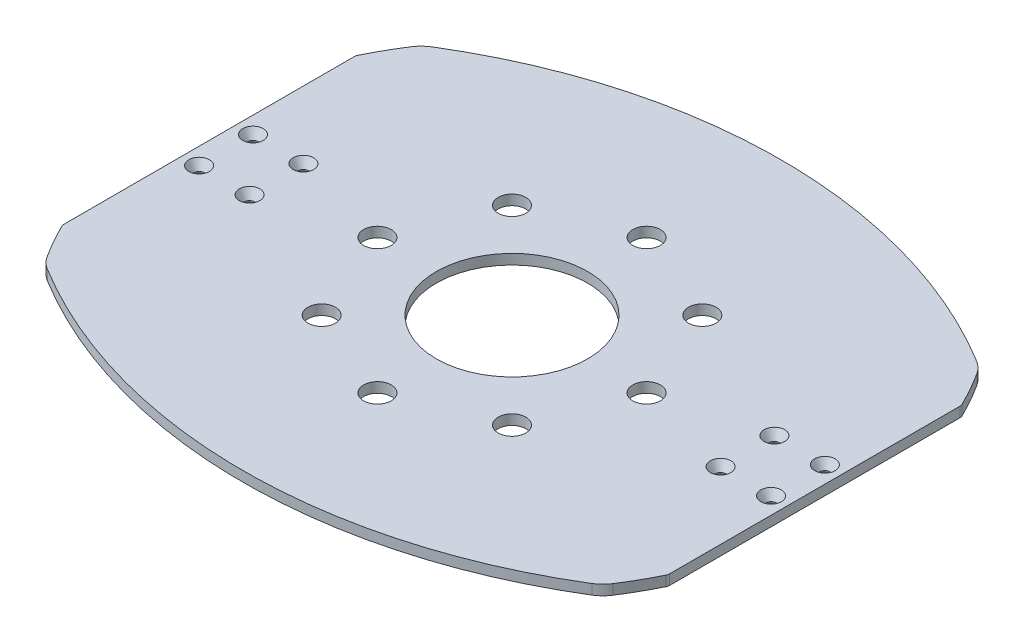
SolidWorks part; units mm, degrees
other "标注1"
sketch "草图6" plane through (-90, 3, -90) normal (0, 1, 0) x (1, 0, 0)
material "Thornel Mat VMA"
ref_plane "前视基准面" through (0, 0, 0) normal (0, 0, 1) x (1, 0, 0)
ref_plane "上视基准面" through (0, 0, 0) normal (0, 1, 0) x (1, 0, 0)
ref_plane "右视基准面" through (0, 0, 0) normal (1, 0, 0) x (0, 0, -1)
sketch "草图2" plane through (0, 0, 0) normal (0, 1, 0) x (1, 0, 0)
  line L1 (-90, 90) -> (90, 90)
  line L2 (-90, 90) -> (-90, -90)
  line L3 (-90, -90) -> (90, -90)
  line L4 (90, 90) -> (90, -90)
  line L5 (0, -90) -> (0, 90) construction
  line L6 (-90, 0) -> (90, 0) construction
  point P40 (0, 0)
  dimension "D1" = 180
  dimension "D2" = 180
extrude "凸台-拉伸1" add sketch "草图2" along normal blind 3
sketch "草图3" plane through (0, 3, 0) normal (0, 1, 0) x (1, 0, 0)
  circle A0 centre (0, 0) radius 40 construction
  circle A1 centre (0, 40) radius 4.1
  circle A2 centre (28.2843, 28.2843) radius 4.1
  circle A3 centre (40, 0) radius 4.1
  circle A4 centre (28.2843, -28.2843) radius 4.1
  circle A5 centre (0, -40) radius 4.1
  circle A6 centre (-28.2843, -28.2843) radius 4.1
  circle A7 centre (-40, 0) radius 4.1
  circle A8 centre (-28.2843, 28.2843) radius 4.1
  point P21 (0, 0)
  dimension "D1" = 80
  dimension "D2" = 8.2
  dimension "D3" = 8
extrude "切除-拉伸1" cut sketch "草图3" against normal blind 3
sketch "草图4" plane through (0, 3, 0) normal (0, 1, 0) x (1, 0, 0)
  circle A0 centre (0, 0) radius 100
  dimension "D1" = 200
extrude "切除-拉伸2" cut sketch "草图4" against normal blind 3 flip side to cut
sketch "草图5" plane through (0, 3, 0) normal (0, 1, 0) x (1, 0, 0)
  line L0 (0, 0) -> (-100, 0) construction
  line L1 (0, 0) -> (0, 95.2788) construction
  line L3 (-85, 8) -> (-70, 8) construction
  line L4 (-85, 8) -> (-85, -8) construction
  line L5 (-85, -8) -> (-70, -8) construction
  line L6 (-70, 8) -> (-70, -8) construction
  line L7 (-77.5, -8) -> (-77.5, 8) construction
  line L8 (-85, 0) -> (-70, 0) construction
  circle A0 centre (0, 0) radius 100 construction
  circle A5 centre (-85, 8) radius 1.55
  circle A6 centre (-70, 8) radius 1.55
  circle A7 centre (-85, -8) radius 1.55
  circle A8 centre (-70, -8) radius 1.55
  circle A9 centre (70, -8) radius 1.55
  circle A10 centre (85, -8) radius 1.55
  circle A11 centre (70, 8) radius 1.55
  circle A12 centre (85, 8) radius 1.55
  point P99 (-77.5, 0)
  dimension "D1" = 16
  dimension "D2" = 15
  dimension "D3" = 77.5
  dimension "D4" = 3.1
extrude "切除-拉伸3" cut sketch "草图5" against normal blind 3
fillet "圆角1" radius 2 8 edges at (-43.589, 1.5, 90) (43.589, 1.5, 90) (-90, 1.5, -43.589) (-90, 1.5, 43.589) (43.589, 1.5, -90) (-43.589, 1.5, -90) (90, 1.5, 43.589) (90, 1.5, -43.589)
sketch "草图7" plane through (0, 3, 0) normal (0, 1, 0) x (1, 0, 0)
  circle A0 centre (0, 0) radius 22.5
  dimension "D1" = 45
extrude "切除-拉伸4" cut sketch "草图7" against normal blind 10
sketch "草图8" plane through (0, 3, 0) normal (0, 1, 0) x (1, 0, 0)
  line L0 (0, 0) -> (0, -75) construction
  line L1 (0, 0) -> (306.2621, 0) construction
  line L2 (-43.1277, -90) -> (43.1277, -90) construction
  line L3 (43.1277, 90) -> (-43.1277, 90) construction
  line L4 (-43.1277, -90) -> (43.1277, -90)
  line L5 (43.1277, 90) -> (-43.1277, 90)
  arc A0 (82.8493, 56) -> (-82.8493, 56) centre (0, -75) ccw
  arc A1 (82.8493, -56) -> (-82.8493, -56) centre (0, 75) cw
  arc A2 (-89.7959, -44.0079) -> (-44.0079, -89.7959) centre (0, 0) ccw construction
  arc A3 (44.0079, -89.7959) -> (89.7959, -44.0079) centre (0, 0) ccw construction
  arc A4 (89.7959, 44.0079) -> (44.0079, 89.7959) centre (0, 0) ccw construction
  arc A5 (-44.0079, 89.7959) -> (-89.7959, 44.0079) centre (0, 0) ccw construction
  arc A6 (-82.8493, -56) -> (-44.0079, -89.7959) centre (0, 0) ccw
  arc A7 (44.0079, -89.7959) -> (82.8493, -56) centre (0, 0) ccw
  arc A8 (82.8493, 56) -> (44.0079, 89.7959) centre (0, 0) ccw
  arc A9 (-44.0079, 89.7959) -> (-82.8493, 56) centre (0, 0) ccw
  arc M18 (-89.7959, -44.0079) -> (-44.0079, -89.7959) centre (0, 0) ccw
  arc M19 (-44.0079, -89.7959) -> (-43.1277, -90) centre (-43.1277, -88) ccw
  line M20 (-43.1277, -90) -> (43.1277, -90)
  arc M21 (43.1277, -90) -> (44.0079, -89.7959) centre (43.1277, -88) ccw
  arc M22 (44.0079, -89.7959) -> (89.7959, -44.0079) centre (0, 0) ccw
  arc M26 (89.7959, 44.0079) -> (44.0079, 89.7959) centre (0, 0) ccw
  arc M27 (44.0079, 89.7959) -> (43.1277, 90) centre (43.1277, 88) ccw
  line M28 (43.1277, 90) -> (-43.1277, 90)
  arc M29 (-43.1277, 90) -> (-44.0079, 89.7959) centre (-43.1277, 88) ccw
  arc M30 (-44.0079, 89.7959) -> (-89.7959, 44.0079) centre (0, 0) ccw
  dimension "D1" = 75
  dimension "D2" = 310
extrude "切除-拉伸5" cut sketch "草图8" against normal blind 10 contours A0 M26 M27 M28 M29 M30 | A1 M22 M18 M19 M20 M21
fillet "圆角2" radius 10 4 edges at (82.8493, 1.5, 56) (-82.8493, 1.5, 56) (-82.8493, 1.5, -56) (82.8493, 1.5, -56)
chamfer "倒角1" distance 1.5 angle 60 8 edges at (-85, 3, -6.45) (85, 3, 6.45) (70, 3, 6.45) (85, 3, -9.55) (70, 3, -9.55) (-70, 3, 9.55) (-85, 3, 9.55) (-70, 3, -6.45)
